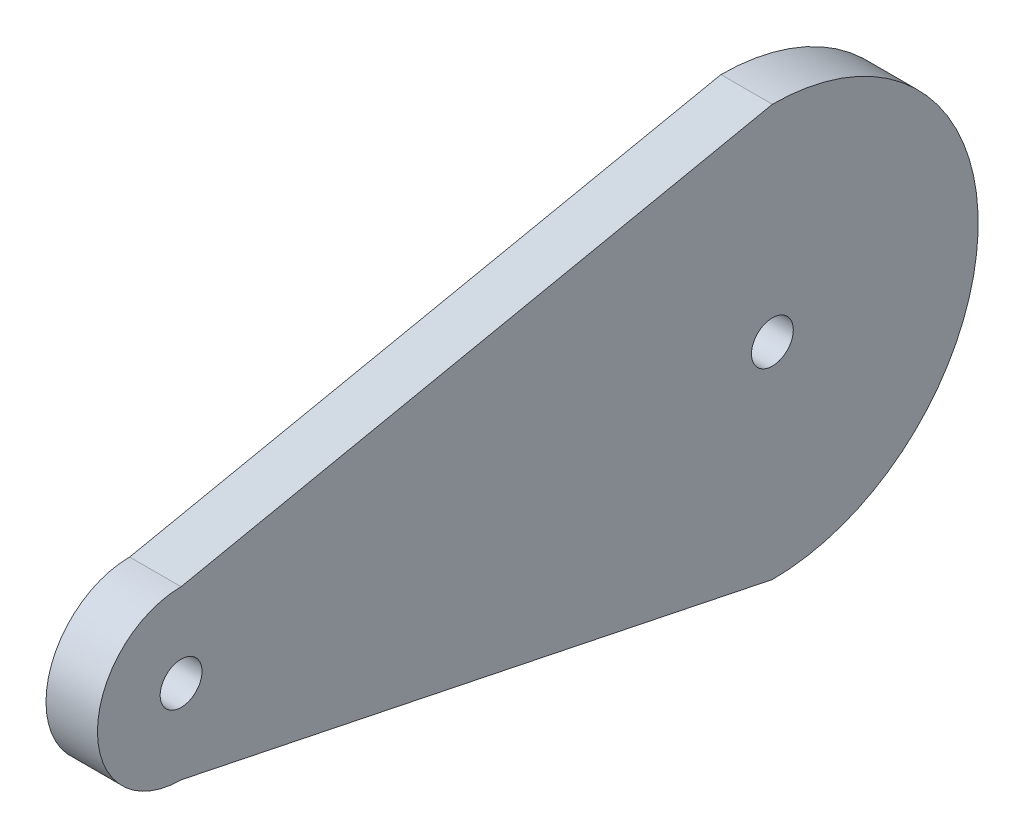
SolidWorks part; units mm, degrees
material "ABS"
ref_plane "Front Plane" through (0, 0, 0) normal (0, 0, 1) x (1, 0, 0)
ref_plane "Top Plane" through (0, 0, 0) normal (0, 1, 0) x (1, 0, 0)
ref_plane "Right Plane" through (0, 0, 0) normal (1, 0, 0) x (0, 0, -1)
sketch "Sketch1" plane through (0, 0, 0) normal (1, 0, 0) x (0, 0, -1)
  line L0 (0, 0) -> (72.9742, 0) construction
  line L1 (0, 10.3233) -> (72.9742, 25.4)
  line L2 (0, -10.3233) -> (72.9742, -25.4)
  circle A0 centre (0, 0) radius 2.5808
  circle A1 centre (0, 0) radius 10.3233
  circle A2 centre (72.9742, 0) radius 25.4
  circle A3 centre (72.9742, 0) radius 2.5808
  dimension "D1" = 72.9742
extrude "Boss-Extrude1" add sketch "Sketch1" along normal blind 6.35
